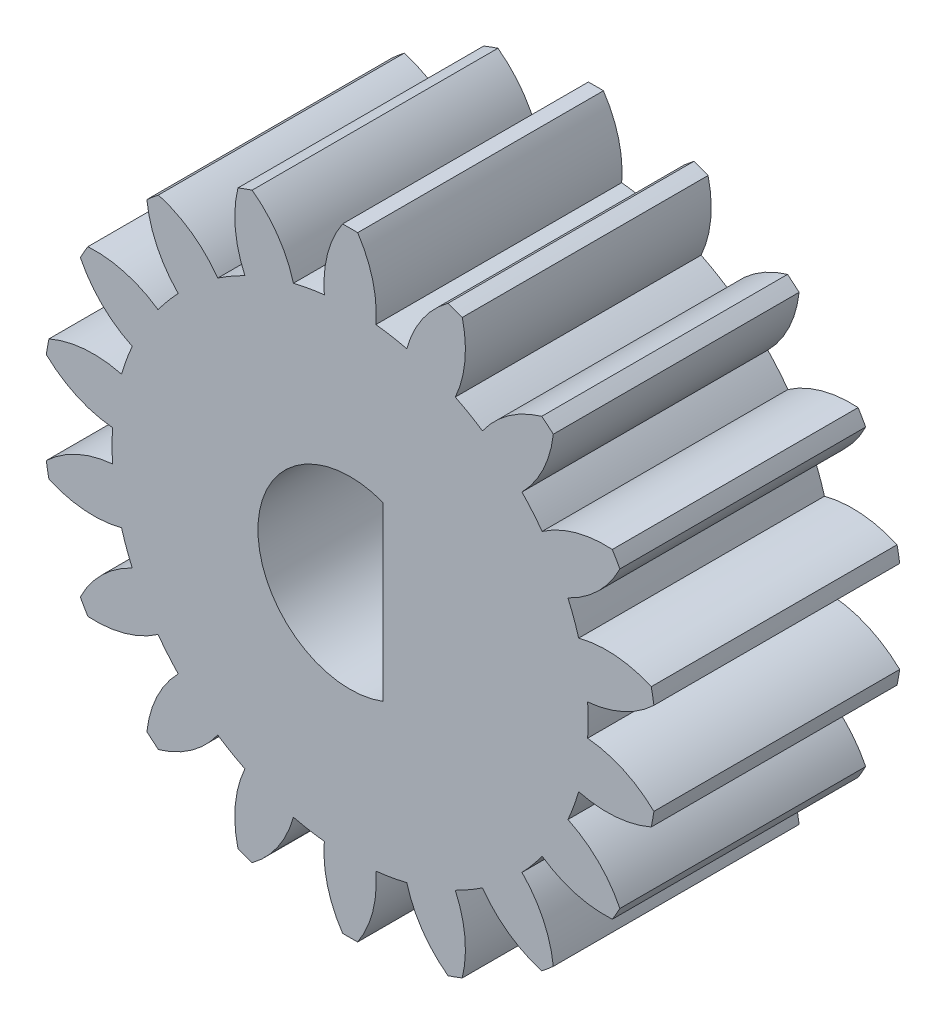
SolidWorks part; units mm, degrees
material "Alumina"
ref_plane "Plane1" through (0, 0, 0) normal (0, 0, 1) x (1, 0, 0)
ref_plane "Plane2" through (0, 0, 0) normal (0, 1, 0) x (1, 0, 0)
ref_plane "Plane3" through (0, 0, 0) normal (1, 0, 0) x (0, 0, -1)
sketch "HoldingSke" plane through (0, 0, 0) normal (0, 1, 0) x (1, 0, 0)
  line L0 (0, 0) -> (1.9021, -0.618)
  line L1 (-15, 0) -> (100, 0) construction
  line L2 (0, 0) -> (-2.1039, 2.3779)
  line L3 (0, 0) -> (-11.863, 4.5341)
  line L4 (0, 0) -> (8.2133, 2.6687)
  line L5 (0, 0) -> (-46.8476, -17.4728)
  line L6 (0, 0) -> (-3.3159, -2.2372)
  line L7 (-2.1039, 2.3779) -> (8.6586, 51.2059)
  line L8 (-76.2, 54.61) -> (-75.7, 54.61)
  line L9 (-71.009, 38.7566) -> (-53.1078, 45.2721)
  line L10 (-76.2, 71.12) -> (104.1128, 71.12)
  line L11 (0, 0) -> (-4, 0)
  line L12 (-76.2, 101.6) -> (-76.181, 101.6)
  line L13 (24.9733, 27.94) -> (52.9518, 28.4284)
  line L14 (24.9733, 27.94) -> (24.9743, 27.94)
  line L15 (24.9733, 27.94) -> (100.4006, 29.5858)
  line L16 (-63.627, -0.5) -> (-12.827, -0.5)
  circle A0 centre (0, 0) radius 1.5
  circle A1 centre (0, 0) radius 3.874
  circle A2 centre (0, 0) radius 37.5
  circle A3 centre (0, 0) radius 1.5
  dimension "MHD" = 7.748
  dimension "Hub_dia" = 75
  dimension "Bore" = 3
  dimension "MBD" = 3
  dimension "Num_teeth" = 18
  dimension "Pitch" = 2
  dimension "Overall_len" = 50
  dimension "Show_teeth" = 18
  dimension "Thickness" = 4
  dimension "OAL" = 50.0001
  dimension "T_dim" = 0.5
  dimension "Ap" = 20
  dimension "H" = 19.05
  dimension "Pitch_radius" = 180.3128
  dimension "Width" = 4
  dimension "Backlash" = 0.019
  dimension "Addendum_fac" = 1
  dimension "Dedendum_fac" = 1.25
  dimension "Clearance_fac" = 0.25
  dimension "Dedendum_add" = 0.001
  dimension "Module" = 0.5
sketch "BasProSke" plane through (0, 0, 0) normal (0, 1, 0) x (1, 0, 0)
  line L0 (-10, 0) -> (60, 0) construction
  line L1 (0, 0) -> (0, 5)
  line L2 (0, 0) -> (4, 0)
  line L3 (4, 0) -> (4, 5)
  line L4 (4, 5) -> (0, 5)
  dimension "Thickness" = 4
  dimension "Diameter" = 10
revolve "Base-Revolve" add sketch "BasProSke" angle 360 about L0
sketch "TooCutSke" plane through (0, 0, 0) normal (1, 0, 0) x (0, 0, -1)
  line L1 (0, 0) -> (0, 107) construction
  line L2 (0, 0) -> (-0.4254, 4.4798) construction
  line L3 (0, 0) -> (-1.5579, 8.835) construction
  line L4 (-0.4254, 4.4798) -> (-0.7789, 4.4175) construction
  arc A0 (0.2553, 3.8656) -> (-0.2553, 3.8656) centre (0, 0) ccw
  arc A1 (0.7686, 4.9663) -> (-0.7686, 4.9663) centre (0, 0) ccw
  circle A2 centre (0, 0) radius 4.5 construction
  circle A3 centre (0, 0) radius 4.2286 construction
  arc A4 (-0.2553, 3.8656) -> (-0.7686, 4.9663) centre (-2.0476, 3.6998) ccw
  arc A5 (0.7686, 4.9663) -> (0.2553, 3.8656) centre (2.0476, 3.6998) ccw
  dimension "Root_dia" = 7.748
  dimension "Overcut_dia" = 10.0508
  dimension "Pitch_dia" = 9
  dimension "Base_dia" = 8.4572
  dimension "Flank_rad" = 1.8
  dimension "Half_ang" = 10
  dimension "Half_CT" = 0.359
extrude "ToothCut" cut sketch "TooCutSke" along normal through all
fillet "Breaks" [suppressed] radius 0.01
fillet "RootFillets" [suppressed] radius 0.126
pattern_circular "TeethCuts" count 18 every 20 about axis through (-10, 0, 0) along (1, 0, 0) of "ToothCut", "RootFillets", "Breaks"
sketch "HubNeaOneSke" plane through (0, 0, 0) normal (-1, 0, 0) x (0, 0, 1)
  circle A0 centre (0, 0) radius 3.874
  dimension "Diameter" = 7.748
extrude "HubNearOne" [suppressed] add sketch "HubNeaOneSke" along normal blind 46.0001
sketch "HubNeaBotSke" plane through (0, 0, 0) normal (-1, 0, 0) x (0, 0, 1)
  circle A0 centre (0, 0) radius 3.874
  dimension "Diameter" = 7.748
extrude "HubNearBoth" [suppressed] add sketch "HubNeaBotSke" along normal blind 23
ref_plane "FarPln" through (4, 0, 0) normal (1, 0, 0) x (0, 0, -1)
sketch "HubFarSke" plane through (4, 0, 0) normal (1, 0, 0) x (0, 0, -1)
  circle A0 centre (0, 0) radius 3.874
  dimension "Diameter" = 7.748
extrude "HubFar" [suppressed] add sketch "HubFarSke" along normal blind 23
sketch "BorSke" plane through (0, 0, 0) normal (1, 0, 0) x (0, 0, -1)
  line L0 (0, -1.5) -> (0, 0.5353) construction
  line L1 (1.4012, 0.5353) -> (-1.4012, 0.5353)
  circle A0 centre (0, 0) radius 1.5
  point P4 (0, 0)
  dimension "Diameter" = 3
extrude "Bore" cut sketch "BorSke" along normal mid plane 100.0001 contours A0 L0 L1 | L0 A0 L1
sketch "KeySke" plane through (0, 0, 0) normal (1, 0, 0) x (0, 0, -1)
  line L0 (-0.6, 0) -> (-0.6, 2)
  line L1 (-0.6, 2) -> (0.6, 2)
  line L2 (0.6, 2) -> (0.6, 0)
  line L3 (0, 0) -> (0, 34) construction
  line L4 (-0.6, 0) -> (0.6, 0)
  dimension "Offset" = 2
  dimension "Width" = 1.2
extrude "Keyway" [suppressed] cut sketch "KeySke" along normal mid plane 100.0001
pattern_circular "Keyway2" [suppressed] count 2 every 90 about axis through (-10, 0, 0) along (1, 0, 0)
move or copy body "Body-Move/Copy1" bodies to move or copy 103 copy no rotation origin (2, 0, 0) rotation axis (0, 0, -1) rotation angle 90
move or copy body "Body-Move/Copy2" bodies to move or copy 104 copy no rotation origin (0, 0, 0) rotation axis (1, 0, 0) rotation angle 90
equation "' \"Module@HoldingSke\" = 6.35"
equation "' \"Num_teeth@HoldingSke\" = 12"
equation "' \"Ap@HoldingSke\" =  20"
equation "' \"Ap@HoldingSke\" = 20"
equation "' \"Width@HoldingSke\" = 0.5 * 25.4"
equation "' \"Hub_dia@HoldingSke\"= 1 * 25.4"
equation "' \"Hub_dia@HoldingSke\" = 1 * 25.4"
equation "' \"Overall_len@HoldingSke\" = 1.0 * 25.4"
equation "' \"Bore@HoldingSke\" = 0.75 * 25.4"
equation "' \"T_dim@HoldingSke\" = 0.1 * 25.4"
equation "' \"Width@KeySke\" = 0.25 * 25.4"
equation "' \"Show_teeth@HoldingSke\" = 13"
equation "' \"Backlash@HoldingSke\" = 0.009 * 25.4"
equation "' \"Addendum_fac@HoldingSke\" = 1.0"
equation "' \"Dedendum_fac@HoldingSke\" = 1.25"
equation "' \"Dedendum_add@HoldingSke\" = 0.00005 * 25.4"
equation "' \"Clearance_fac@HoldingSke\" = 0.25"
equation "\"Pitch@HoldingSke\" = 1 / \"Module@HoldingSke\""
equation "\"Overcut_dia@TooCutSke\" = (\"Num_teeth@HoldingSke\" + 2 * \"Addendum_fac@HoldingSke\") / \"Pitch@HoldingSke\" + 0.002 * 25.4"
equation "\"Pitch_dia@TooCutSke\" = \"Num_teeth@HoldingSke\" / \"Pitch@HoldingSke\""
equation "\"Base_dia@TooCutSke\" = \"Num_teeth@HoldingSke\" / \"Pitch@HoldingSke\" * cos((\"Ap@HoldingSke\"  * 3.14159265 / 180))"
equation "\"Root_dia@TooCutSke\" = (\"Num_teeth@HoldingSke\" + 2) / \"Pitch@HoldingSke\" - 2 * (\"Addendum_fac@HoldingSke\" + \"Dedendum_fac@HoldingSke\") / \"Pitch@HoldingSke\" - \"Dedendum_add@HoldingSke\" * 2"
equation "\"Half_ang@TooCutSke\" = 180 / \"Num_teeth@HoldingSke\""
equation "\"Half_CT@TooCutSke\" = \"Num_teeth@HoldingSke\" / \"Pitch@HoldingSke\" * sin((3.14159265 / 2 / \"Num_teeth@HoldingSke\")) / 2 - 7 * \"Backlash@HoldingSke\" / 4"
equation "\"Flank_rad@TooCutSke\" = \"Num_teeth@HoldingSke\" / \"Pitch@HoldingSke\" / 5"
equation "\"Radius@RootFillets\" = \"Clearance_fac@HoldingSke\" / \"Pitch@HoldingSke\" + \"Dedendum_add@HoldingSke\""
equation "\"Break_rad@Breaks\" = 0.02 / \"Pitch@HoldingSke\""
equation "\"Thickness@HoldingSke\" = \"Width@HoldingSke\""
equation "\"OAL@HoldingSke\" = \"Thickness@HoldingSke\""
equation "\"MHD@HoldingSke\" = (\"Num_teeth@HoldingSke\" + 2) / \"Pitch@HoldingSke\" - 2 * (\"Addendum_fac@HoldingSke\" + \"Dedendum_fac@HoldingSke\")  / \"Pitch@HoldingSke\" - \"Dedendum_add@HoldingSke\" * 2"
equation "\"MBD@HoldingSke\" = (\"Num_teeth@HoldingSke\" + 2) / \"Pitch@HoldingSke\" - 2 * (\"Addendum_fac@HoldingSke\" + \"Dedendum_fac@HoldingSke\")  / \"Pitch@HoldingSke\" - \"Dedendum_add@HoldingSke\" * 2 - 0.002 * 25.4"
equation "\"MHD@HoldingSke\" = ((sgn( \"MHD@HoldingSke\" - \"Hub_dia@HoldingSke\" )-1)*( \"MHD@HoldingSke\" - \"Hub_dia@HoldingSke\" ))/-2+ \"Hub_dia@HoldingSke\""
equation "\"MBD@HoldingSke\" = ((sgn( \"MBD@HoldingSke\" - \"Bore@HoldingSke\" )-1)*( \"MBD@HoldingSke\" - \"Bore@HoldingSke\" ))/-2+ \"Bore@HoldingSke\""
equation "\"OAL@HoldingSke\" = ((sgn( \"OAL@HoldingSke\" - \"Overall_len@HoldingSke\" )+1)*( \"OAL@HoldingSke\" - \"Overall_len@HoldingSke\" ))/2 + \"Overall_len@HoldingSke\" + 0.000002 * 25.4"
equation "\"Num_teeth@TeethCuts\" = int( \"Show_teeth@HoldingSke\" ) + 1"
equation "\"Num_teeth@TeethCuts\" = ((sgn( \"Num_teeth@TeethCuts\" - \"Num_teeth@HoldingSke\" )-1)*( \"Num_teeth@TeethCuts\" - \"Num_teeth@HoldingSke\" ))/-2+ \"Num_teeth@HoldingSke\""
equation "\"Num_teeth@TeethCuts\" = ((sgn( \"Num_teeth@TeethCuts\" - 2.0)+1)*( \"Num_teeth@TeethCuts\" - 2.0))/2 +2.0"
equation "\"Angle@TeethCuts\" = 360.0 / \"Num_teeth@HoldingSke\""
equation "\"Diameter@BasProSke\" = (\"Num_teeth@HoldingSke\" + 2 * \"Addendum_fac@HoldingSke\") / \"Pitch@HoldingSke\""
equation "\"Thickness@BasProSke\"  = \"Thickness@HoldingSke\""
equation "' \"Fillet_rad@BasProSke\" =  \"Thickness@HoldingSke\" * 0.05"
equation "' \"Fillet_rad@BasProSke\" = \"Thickness@HoldingSke\" * 0.05"
equation "\"MHD@HoldingSke\" = ((sgn( \"MHD@HoldingSke\" - \"Root_dia@TooCutSke\" )-1)*( \"MHD@HoldingSke\" - \"Root_dia@TooCutSke\" ))/-2+ \"Root_dia@TooCutSke\""
equation "\"Diameter@HubNeaOneSke\" = \"MHD@HoldingSke\""
equation "\"Length@HubNearOne\" = \"OAL@HoldingSke\" - \"Thickness@BasProSke\""
equation "\"Diameter@HubNeaBotSke\" = \"MHD@HoldingSke\""
equation "\"Length@HubNearBoth\" = ( \"OAL@HoldingSke\" - \"Thickness@BasProSke\" ) / 2.0"
equation "\"Thickness@FarPln\" = \"Thickness@BasProSke\""
equation "\"Diameter@HubFarSke\" = \"MHD@HoldingSke\""
equation "\"Length@HubFar\" = ( \"OAL@HoldingSke\" - \"Thickness@BasProSke\" ) / 2.0"
equation "\"Diameter@BorSke\" = \"MBD@HoldingSke\""
equation "\"D1@Bore\" = \"OAL@HoldingSke\" * 2.0"
equation "\"D1@Keyway\" = \"OAL@HoldingSke\" * 2.0"
equation "\"Offset@KeySke\" = \"T_dim@HoldingSke\" + \"MBD@HoldingSke\" / 2.0"
